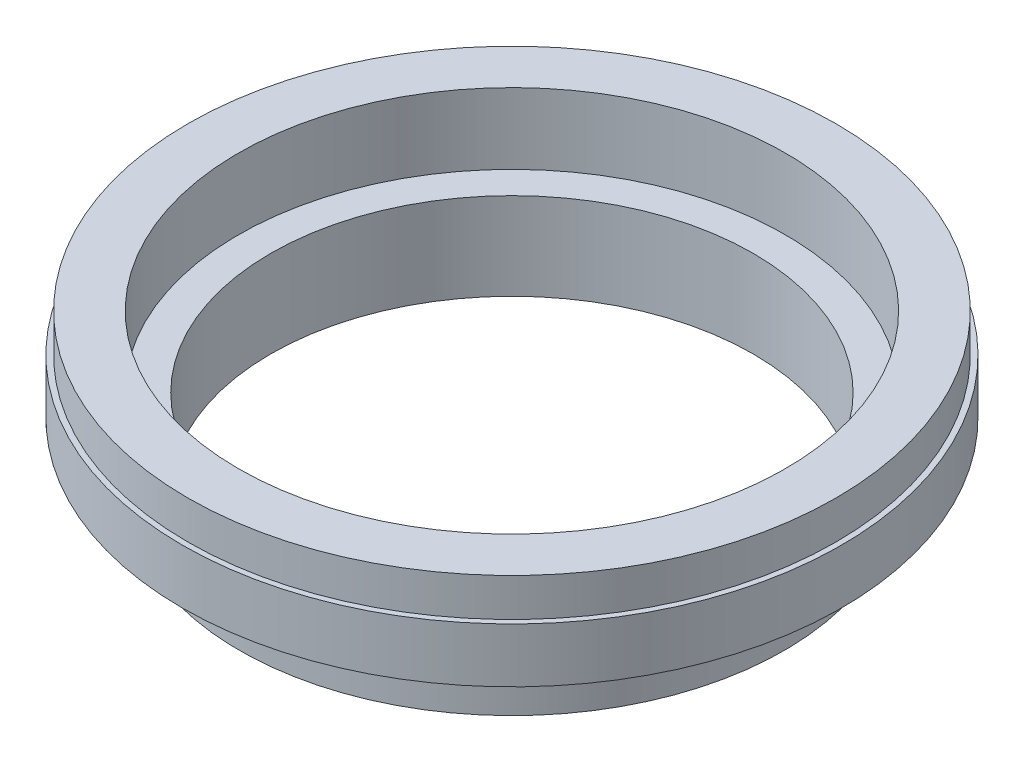
SolidWorks part; units mm, degrees
ref_plane "Front Plane" through (0, 0, 0) normal (0, 0, 1) x (1, 0, 0)
ref_plane "Top Plane" through (0, 0, 0) normal (0, 1, 0) x (1, 0, 0)
ref_plane "Right Plane" through (0, 0, 0) normal (1, 0, 0) x (0, 0, -1)
sketch "Sketch1" plane through (0, 0, 0) normal (0, 1, 0) x (1, 0, 0)
  circle A0 centre (0, 0) radius 12.7
  circle A1 centre (0, 0) radius 11.25
  dimension "D1" = 25.4
  dimension "D2" = 22.5
extrude "Boss-Extrude1" add sketch "Sketch1" along normal blind 3.048
sketch "Sketch2" plane through (0, 3.048, 0) normal (0, 1, 0) x (1, 0, 0)
  circle A0 centre (0, 0) radius 15.367
  dimension "D1" = 30.734
extrude "Boss-Extrude2" add sketch "Sketch2" along normal blind 2.54
sketch "Sketch3" plane through (0, 5.588, 0) normal (0, 1, 0) x (1, 0, 0)
  circle A0 centre (0, 0) radius 15.113
  dimension "D1" = 30.226
extrude "Boss-Extrude3" add sketch "Sketch3" along normal blind 1.778
sketch "Sketch4" plane through (0, 3.048, 0) normal (0, -1, 0) x (1, 0, 0)
  circle A0 centre (0, 0) radius 11.25
  circle A1 centre (0, 0) radius 11.25 construction
extrude "Cut-Extrude1" cut sketch "Sketch4" against normal up to surface (4.318 mm away) up to face at (0, 7.366, 15.113)
sketch "Sketch5" plane through (0, 7.366, 0) normal (0, 1, 0) x (1, 0, 0)
  circle A0 centre (0, 0) radius 12.75
  dimension "D1" = 25.5
extrude "Cut-Extrude2" cut sketch "Sketch5" against normal blind 3.302
